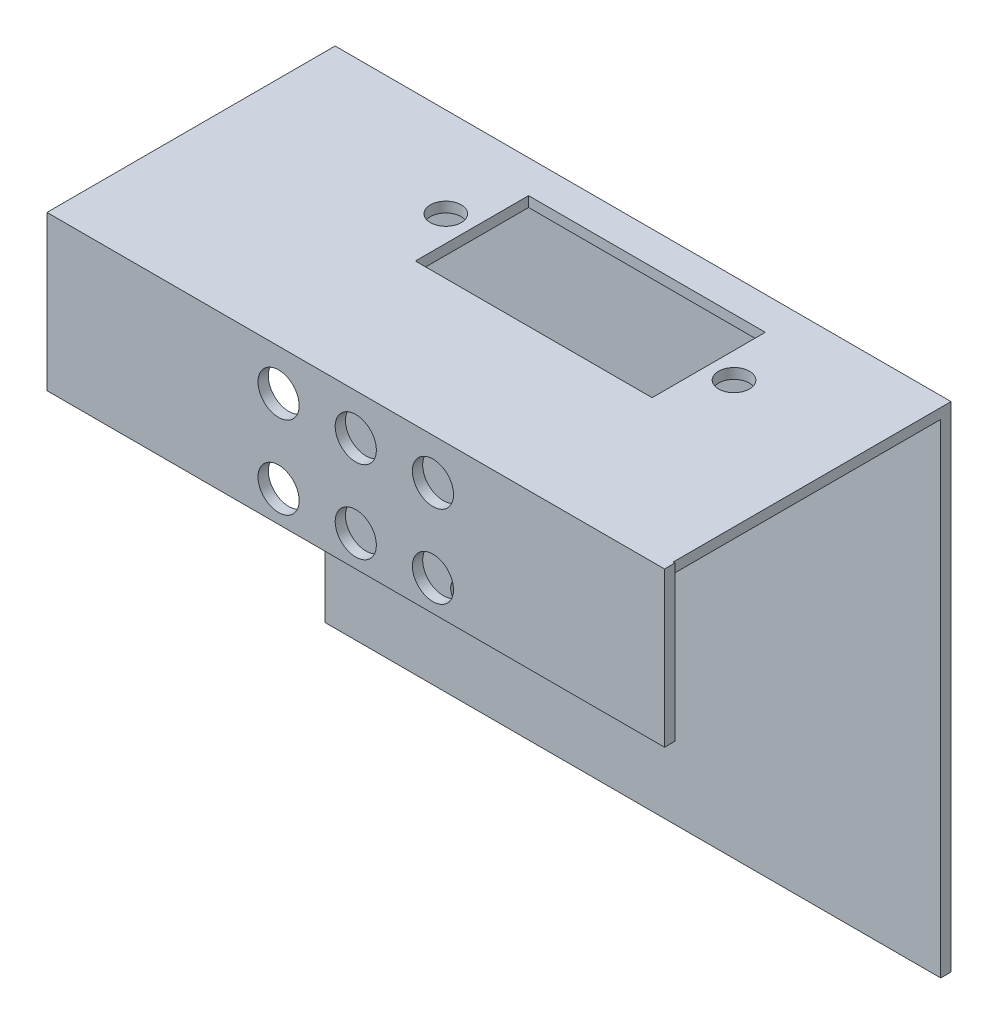
SolidWorks part; units mm, degrees
ref_plane "Plan de face" through (0, 0, 0) normal (0, 0, 1) x (1, 0, 0)
ref_plane "Plan de dessus" through (0, 0, 0) normal (0, 1, 0) x (1, 0, 0)
ref_plane "Plan de droite" through (0, 0, 0) normal (1, 0, 0) x (0, 0, -1)
sketch "Esquisse1" plane through (0, 0, 0) normal (0, 0, 1) x (1, 0, 0)
  line L1 (30, 7.5) -> (-30, 7.5)
  line L2 (30, 7.5) -> (30, -7.5)
  line L3 (30, -7.5) -> (-30, -7.5)
  line L4 (-30, 7.5) -> (-30, -7.5)
  line L5 (30, 7.5) -> (-30, -7.5) construction
  line L6 (30, -7.5) -> (-30, 7.5) construction
  point P0 (0, 0)
  dimension "D1" = 60
  dimension "D2" = 15
extrude "Boss.-Extru.1" add sketch "Esquisse1" along normal blind 1
ref_plane "Plan1" through (0, 7.5, 0) normal (0, 1, 0) x (1, 0, 0)
sketch "Esquisse2" plane through (0, 7.5, 0) normal (0, 1, 0) x (1, 0, 0)
  line L0 (-30.004, 0) -> (-30.004, 27)
  line L1 (-30.004, 27) -> (29.8328, 27)
  line L2 (29.8328, 27) -> (29.8328, 0)
  line L3 (-30.004, 0) -> (29.8328, 0)
  dimension "D1" = 27
extrude "Boss.-Extru.2" add sketch "Esquisse2" against normal blind 1
ref_plane "Plan2" through (0, 0, -27) normal (0, 0, 1) x (1, 0, 0)
sketch "Esquisse4" plane through (0, 0, -27) normal (0, 0, 1) x (1, 0, 0)
  line L0 (29.8328, 6.5) -> (29.8328, -40.5)
  line L1 (29.8328, -40.5) -> (-30.004, -40.5)
  line L2 (-30.004, -40.5) -> (-30.004, 6.5)
  line L3 (29.8328, 6.5) -> (-30.004, 6.5)
  dimension "D1" = 47
extrude "Boss.-Extru.3" add sketch "Esquisse4" along normal blind 1
sketch "Esquisse6" plane through (0, 0, 1) normal (0, 0, 1) x (1, 0, 0)
  line L0 (-30, -7.5) -> (30, -7.5) construction
  line L1 (11.5, 7.5) -> (-11.5, 7.5)
  line L2 (11.5, 7.5) -> (11.5, -7.5)
  line L3 (11.5, -7.5) -> (-11.5, -7.5)
  line L4 (-11.5, 7.5) -> (-11.5, -7.5)
  line L5 (11.5, 7.5) -> (-11.5, -7.5) construction
  line L6 (11.5, -7.5) -> (-11.5, 7.5) construction
  line L7 (-30, 7.5) -> (-30, -7.5) construction
  line L8 (30, -7.5) -> (30, 7.5) construction
  line L9 (-15.0881, -0.5) -> (25.8229, -0.5) construction
  line L10 (15.4, 7.5) -> (-15.4, 7.5) construction
  circle A0 centre (-7.5, 3.5) radius 2
  circle A1 centre (0, 3.5) radius 2
  circle A2 centre (10.2712, 5.4008) radius 0.3964
  circle A3 centre (7.5, 3.5) radius 2
  circle A4 centre (7.5, -4.5) radius 2
  circle A5 centre (0, -4.5) radius 2
  circle A6 centre (-7.5, -4.5) radius 2
  point P0 (0, 0)
  dimension "D3" = 4
  dimension "D4" = 4
  dimension "D5" = 4
  dimension "D8" = 4
  dimension "D9" = 4
  dimension "D1" = 18.5
  dimension "D2" = 18.5
  dimension "D6" = 4
  dimension "D7" = 4
  dimension "D10" = 4
  dimension "D11" = 11.5
  dimension "D12" = 8
extrude "Enlèv. mat.-Extru.5" cut sketch "Esquisse6" against normal blind 1 contours A0 | A1 | A3 | A4 | A5 | A6
sketch "Esquisse8" plane through (0, 7.5, 0) normal (0, 1, 0) x (1, 0, 0)
  line L1 (-8.0159, 23.8074) -> (14.9841, 23.8074)
  line L2 (-8.0159, 23.8074) -> (-8.0159, 12.8074)
  line L3 (-8.0159, 12.8074) -> (14.9841, 12.8074)
  line L4 (14.9841, 23.8074) -> (14.9841, 12.8074)
  line L5 (-8.0159, 23.8074) -> (14.9841, 12.8074) construction
  line L6 (-8.0159, 12.8074) -> (14.9841, 23.8074) construction
  point P0 (3.4841, 18.3074)
  dimension "D1" = 23
  dimension "D2" = 11
extrude "Enlèv. mat.-Extru.7" cut sketch "Esquisse8" against normal blind 1
sketch "Esquisse9" plane through (0, 7.5, 0) normal (0, 1, 0) x (1, 0, 0)
  line L0 (-8.0159, 23.8074) -> (-8.0159, 12.8074) construction
  line L1 (14.9841, 12.8074) -> (14.9841, 23.8074) construction
  circle A0 centre (17.4841, 18.265) radius 1.5
  circle A1 centre (-10.5159, 18.265) radius 1.5
  point P6 (-10.5159, 18.265)
  point P9 (17.4841, 18.265)
  dimension "D1" = 3
  dimension "D2" = 3
  dimension "D3" = 2.5
  dimension "D4" = 2.5
extrude "Enlèv. mat.-Extru.8" cut sketch "Esquisse9" against normal blind 1
sketch "Esquisse10" plane through (0, 0, -27) normal (0, 0, -1) x (-1, 0, 0)
  circle A0 centre (16.5283, -31.4907) radius 1.25
  circle A1 centre (16.0743, -9.9955) radius 1.25
  dimension "D1" = 2.5
  dimension "D2" = 2.5
  dimension "D3" = 21.5
extrude "Enlèv. mat.-Extru.9" cut sketch "Esquisse10" against normal blind 1
